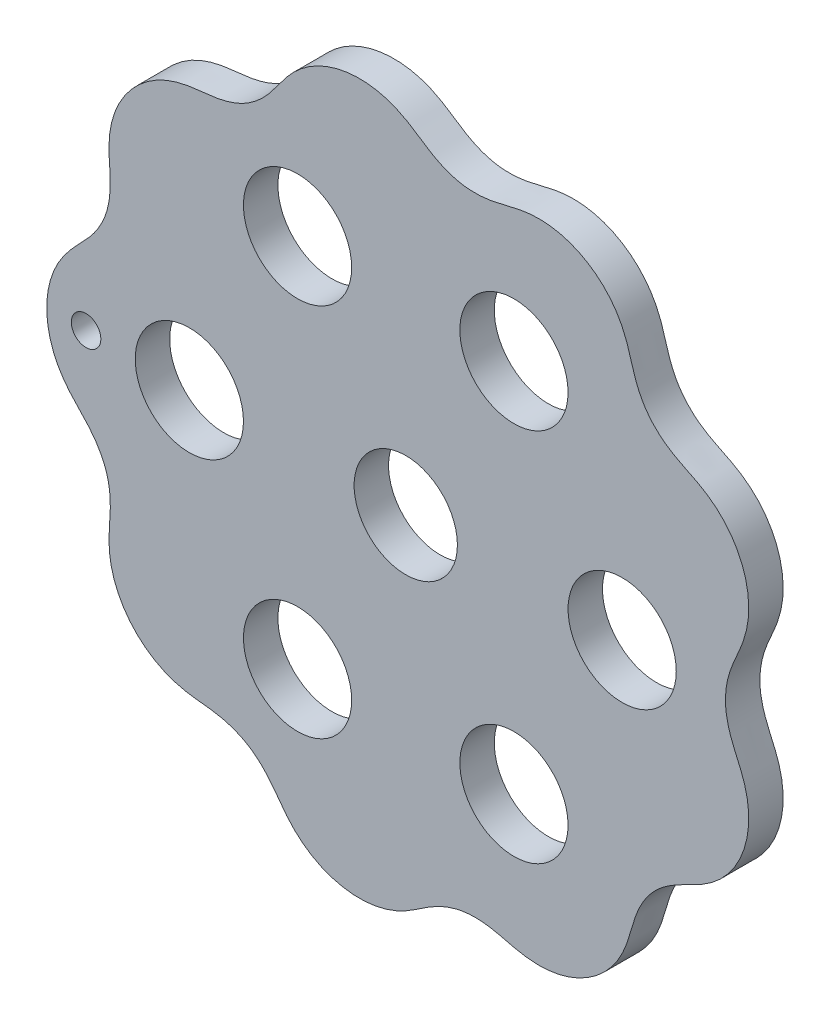
SolidWorks part; units mm, degrees
ref_plane "Front Plane" through (0, 0, 0) normal (0, 0, 1) x (1, 0, 0)
ref_plane "Top Plane" through (0, 0, 0) normal (0, 1, 0) x (1, 0, 0)
ref_plane "Right Plane" through (0, 0, 0) normal (1, 0, 0) x (0, 0, -1)
sketch "Sketch1" plane through (0, 0, 0) normal (0, 0, 1) x (1, 0, 0)
  line L0 (-73, 0) -> (65, 0) construction
  spline S0 degree 4 poles (61.3073, -34.2273) (61.493, -34.1034) (61.8608, -33.8502) (62.401, -33.4542) (63.0962, -32.8933) (63.7568, -32.3065) (64.3822, -31.6959) (64.9718, -31.0638) (65.5256, -30.4127) (66.049, -29.737) (66.541, -29.038) (67.0007, -28.3174) (67.4273, -27.5767) (67.8199, -26.8174) (68.178, -26.0413) (68.5008, -25.2499) (68.7877, -24.4447) (69.0381, -23.6275) (69.2514, -22.7998) (69.4273, -21.9633) (69.5651, -21.1198) (69.6645, -20.2708) (69.7176, -19.5248) (69.7387, -18.8842) (69.74, -18.3502) (69.7313, -17.923) (69.7127, -17.4962) (69.6843, -17.0698) (69.6462, -16.6443) (69.5983, -16.2198) (69.5407, -15.7964) (69.4819, -15.4273) (69.4255, -15.1119) (69.3746, -14.8498) (69.3316, -14.6406) (69.2862, -14.4319) (69.2444, -14.2497) (69.2072, -14.0939) (69.1753, -13.9642) (69.1492, -13.8607) (69.1228, -13.7581) (69.0951, -13.6533) (69.0665, -13.5475) (69.0433, -13.4628) (69.0257, -13.3989) (69.0055, -13.3279) (68.9819, -13.2466) (68.944, -13.1175) (68.9076, -12.9939) (68.9636, -13.1823) (68.9277, -13.0626) (68.8813, -12.9088) (68.8479, -12.7995) (68.8281, -12.7378) (68.803, -12.6599) (68.7773, -12.5799) (68.7411, -12.4684) (68.7054, -12.3603) (68.6699, -12.2562) (68.6201, -12.1128) (68.5664, -11.9595) (68.5026, -11.7817) (68.4128, -11.5396) (68.3173, -11.2884) (68.2213, -11.0447) (68.1025, -10.7498) (67.9816, -10.457) (67.7962, -10.0189) (67.5427, -9.4377) (67.242, -8.7617) (66.9007, -7.9882) (66.6001, -7.2806) (66.3428, -6.6384) (66.1272, -6.0623) (65.9496, -5.5542) (65.7844, -5.042) (65.6328, -4.5255) (65.4957, -4.005) (65.374, -3.4807) (65.2514, -2.868) (65.1386, -2.1654) (65.0487, -1.3722) (64.9973, -0.4888) (64.9947, 0.3961) (65.0411, 1.2797) (65.1356, 2.1595) (65.2772, 3.0327) (65.4938, 4.0386) (65.8091, 5.1683) (66.3609, 6.7584) (67.1956, 8.6804) (68.1864, 10.8265) (69.0064, 13.131) (69.4921, 15.2329) (69.7787, 17.6218) (69.7586, 20.2836) (69.2421, 23.3843) (67.9898, 26.7805) (66.1004, 29.9051) (63.9856, 32.2244) (61.9632, 33.8331) (59.9244, 35.1173) (58.0026, 36.1114) (55.773, 37.1453) (53.1577, 38.6272) (50.6634, 40.6124) (48.1772, 43.6332) (46.5494, 47.2486) (45.6788, 50.853) (44.4877, 54.3714) (42.9782, 57.2636) (40.8374, 60.0002) (38.0491, 62.4028) (34.8563, 64.2263) (31.375, 65.4056) (27.9067, 65.8635) (24.5909, 65.6864) (21.6065, 65.0508) (18.9163, 64.3231) (15.9988, 63.7742) (12.8476, 63.668) (9.7288, 64.2152) (6.802, 65.3881) (4.2464, 66.8988) (1.967, 68.5024) (-0.6182, 70.1232) (-3.6716, 71.428) (-7.0863, 72.1888) (-10.7608, 72.2765) (-14.3856, 71.6601) (-17.8293, 70.3608) (-20.7797, 68.5257) (-23.1904, 66.3276) (-25.5166, 63.4314) (-27.5659, 60.3413) (-30.3273, 57.4962) (-33.6934, 55.5025) (-36.7147, 54.4849) (-39.3098, 54.0465) (-41.384, 53.8369) (-43.1619, 53.6423) (-44.6386, 53.4201) (-46.629, 52.9929) (-49.081, 52.1759) (-51.8634, 50.724) (-54.7375, 48.4165) (-57.1178, 45.5984) (-58.9152, 42.3728) (-59.9875, 39.0487) (-60.4067, 35.7907) (-60.3256, 32.7522) (-60.0723, 29.9661) (-60.0138, 26.959) (-60.4508, 23.7661) (-61.5496, 20.7238) (-63.2538, 17.9882) (-64.9898, 15.9872) (-66.447, 14.4994) (-67.6572, 13.2246) (-68.5997, 12.1464) (-69.5368, 10.932) (-70.4328, 9.5635) (-71.25, 8.0297) (-71.9504, 6.3291) (-72.4801, 4.5677) (-72.8354, 2.7632) (-72.994, 1.139) (-73.0156, -0.2846) (-72.952, -1.4991) (-72.8589, -2.3772) (-72.7459, -3.1254) (-72.6296, -3.7451) (-72.5233, -4.2382) (-72.4038, -4.7283) (-72.2712, -5.2149) (-72.1256, -5.6978) (-71.9669, -6.1766) (-71.7954, -6.651) (-71.6111, -7.1205) (-71.4141, -7.5849) (-71.2047, -8.0437) (-71.0106, -8.4401) (-70.8366, -8.776) (-70.6867, -9.0532) (-70.5638, -9.2734) (-70.4379, -9.4919) (-70.3091, -9.7087) (-70.1775, -9.9238) (-70.0431, -10.1371) (-69.9229, -10.3223) (-69.8185, -10.4796) (-69.712, -10.637) (-69.6251, -10.7635) (-69.5368, -10.8888) (-69.4726, -10.9795) (-69.4329, -11.0351) (-69.3882, -11.0965) (-69.3015, -11.2146) (-69.1776, -11.3824) (-69.3167, -11.195) (-69.2384, -11.3) (-69.142, -11.4289) (-69.0732, -11.5202) (-69.0334, -11.5715) (-68.9831, -11.6363) (-68.9314, -11.7028) (-68.8591, -11.7955) (-68.7884, -11.8852) (-68.7193, -11.9709) (-68.6232, -12.0889) (-68.52, -12.2148) (-68.399, -12.3604) (-68.2314, -12.5575) (-68.0554, -12.7613) (-67.8814, -12.9579) (-67.6684, -13.1949) (-67.4542, -13.4292) (-67.1294, -13.7782) (-66.6913, -14.2385) (-66.1765, -14.7721) (-65.5899, -15.3836) (-65.0645, -15.9471) (-64.6022, -16.464) (-64.202, -16.9328) (-63.8609, -17.3507) (-63.4474, -17.8834) (-63.0529, -18.4304) (-62.6798, -18.9923) (-62.2852, -19.643) (-61.9391, -20.2663) (-61.5838, -20.983) (-61.234, -21.7977) (-60.9299, -22.6305) (-60.6724, -23.4789) (-60.4617, -24.34) (-60.2975, -25.2111) (-60.159, -26.2326) (-60.0706, -27.405) (-60.054, -28.7251) (-60.1161, -30.1879) (-60.1943, -31.2829) (-60.2441, -32.0131) (-60.2664, -32.3783) knots 0 0 0 0 0 0.002911 0.005822 0.008733 0.011644 0.01443 0.017216 0.020002 0.022788 0.025574 0.02836 0.031145 0.033931 0.036717 0.039503 0.042289 0.045074 0.04786 0.050646 0.053432 0.056218 0.059003 0.060396 0.061789 0.063182 0.064575 0.065968 0.067361 0.068753 0.070146 0.071539 0.072235 0.072932 0.073628 0.074324 0.075021 0.075369 0.075717 0.076065 0.076413 0.076762 0.07711 0.077458 0.077632 0.077806 0.07798 0.078154 0.078503 0.078847 0.079019 0.079192 0.079536 0.079881 0.080226 0.080398 0.08057 0.081259 0.081604 0.081948 0.082638 0.083327 0.084016 0.085394 0.086083 0.086773 0.088151 0.089529 0.092286 0.095043 0.097799 0.100556 0.102311 0.104065 0.10582 0.107575 0.109329 0.111084 0.112839 0.114593 0.117477 0.120361 0.123244 0.126128 0.129011 0.131894 0.134777 0.137661 0.142422 0.147183 0.156706 0.164976 0.173246 0.179012 0.184777 0.196307 0.207838 0.219769 0.231702 0.243634 0.2485 0.253366 0.263098 0.271825 0.280552 0.292488 0.304425 0.322381 0.331611 0.340841 0.352772 0.364705 0.376636 0.388536 0.400436 0.412336 0.421971 0.431607 0.440152 0.448697 0.460602 0.472507 0.481053 0.489598 0.499233 0.508869 0.520769 0.532669 0.544569 0.5565 0.568433 0.580364 0.589594 0.598824 0.61678 0.628717 0.640652 0.64938 0.658107 0.662973 0.667839 0.672705 0.677571 0.689503 0.701436 0.713367 0.725341 0.737315 0.749288 0.758622 0.767957 0.776873 0.785788 0.797766 0.809744 0.81866 0.827576 0.832243 0.83691 0.841577 0.846245 0.852231 0.858218 0.864205 0.870192 0.876179 0.882166 0.885454 0.888743 0.892032 0.893676 0.89532 0.896965 0.898609 0.900253 0.901898 0.903542 0.905186 0.906831 0.908475 0.910119 0.911763 0.912586 0.913408 0.91423 0.915052 0.915874 0.916696 0.917518 0.91834 0.918751 0.919162 0.919984 0.920396 0.920601 0.920807 0.921012 0.921218 0.921629 0.921974 0.922147 0.922319 0.922665 0.92301 0.923355 0.923528 0.923701 0.924391 0.924737 0.925082 0.925773 0.926463 0.927154 0.928535 0.929226 0.929917 0.931298 0.932679 0.935442 0.938205 0.940968 0.94373 0.945489 0.947247 0.949006 0.950765 0.954282 0.95604 0.957799 0.960688 0.963577 0.966467 0.969356 0.972245 0.975134 0.978022 0.980911 0.985683 0.990456 0.995228 1 1 1 1 1 construction
  spline S1 degree 4 poles (65, 0) (65, 0.2095) (65.0075, 0.6401) (65.0423, 1.2912) (65.1356, 2.1595) (65.2772, 3.0327) (65.4938, 4.0386) (65.8091, 5.1683) (66.3609, 6.7584) (67.1956, 8.6804) (68.1864, 10.8265) (69.0064, 13.131) (69.4921, 15.2329) (69.7787, 17.6218) (69.7586, 20.2836) (69.2421, 23.3843) (67.9898, 26.7805) (66.1004, 29.9051) (63.9856, 32.2244) (61.9632, 33.8331) (59.9244, 35.1173) (58.0026, 36.1114) (55.773, 37.1453) (53.1577, 38.6272) (50.6634, 40.6124) (48.1772, 43.6332) (46.5494, 47.2486) (45.6788, 50.853) (44.4877, 54.3714) (42.9782, 57.2636) (40.8374, 60.0002) (38.0491, 62.4028) (34.8563, 64.2263) (31.375, 65.4056) (27.9067, 65.8635) (24.5909, 65.6864) (21.6065, 65.0508) (18.9163, 64.3231) (15.9988, 63.7742) (12.8476, 63.668) (9.7288, 64.2152) (6.802, 65.3881) (4.2464, 66.8988) (1.967, 68.5024) (-0.6182, 70.1232) (-3.6716, 71.428) (-7.0863, 72.1888) (-10.7608, 72.2765) (-14.3856, 71.6601) (-17.8293, 70.3608) (-20.7797, 68.5257) (-23.1904, 66.3276) (-25.5166, 63.4314) (-27.5659, 60.3413) (-30.3273, 57.4962) (-33.6934, 55.5025) (-36.7147, 54.4849) (-39.3098, 54.0465) (-41.384, 53.8369) (-43.1619, 53.6423) (-44.6386, 53.4201) (-46.629, 52.9929) (-49.081, 52.1759) (-51.8634, 50.724) (-54.7375, 48.4165) (-57.1178, 45.5984) (-58.9152, 42.3728) (-59.9875, 39.0487) (-60.4067, 35.7907) (-60.3256, 32.7522) (-60.0723, 29.9661) (-60.0138, 26.959) (-60.4508, 23.7661) (-61.5496, 20.7238) (-63.2538, 17.9882) (-64.9898, 15.9872) (-66.447, 14.4994) (-67.6572, 13.2246) (-68.5997, 12.1464) (-69.5368, 10.932) (-70.4328, 9.5635) (-71.25, 8.0297) (-71.9504, 6.3291) (-72.4801, 4.5677) (-72.8354, 2.7632) (-72.9698, 1.3871) (-72.9999, 0.4657) (-73, 0.0033) (-73, 0) knots 0.123395 0.123395 0.123395 0.123395 0.123395 0.126128 0.129011 0.131894 0.134777 0.137661 0.142422 0.147183 0.156706 0.164976 0.173246 0.179012 0.184777 0.196307 0.207838 0.219769 0.231702 0.243634 0.2485 0.253366 0.263098 0.271825 0.280552 0.292488 0.304425 0.322381 0.331611 0.340841 0.352772 0.364705 0.376636 0.388536 0.400436 0.412336 0.421971 0.431607 0.440152 0.448697 0.460602 0.472507 0.481053 0.489598 0.499233 0.508869 0.520769 0.532669 0.544569 0.5565 0.568433 0.580364 0.589594 0.598824 0.61678 0.628717 0.640652 0.64938 0.658107 0.662973 0.667839 0.672705 0.677571 0.689503 0.701436 0.713367 0.725341 0.737315 0.749288 0.758622 0.767957 0.776873 0.785788 0.797766 0.809744 0.81866 0.827576 0.832243 0.83691 0.841577 0.846245 0.852231 0.858218 0.864205 0.870192 0.876179 0.882166 0.882209 0.882209 0.882209 0.882209 0.882209 construction
  spline S2 degree 4 poles (65, 0) (65, -0.2095) (65.0075, -0.6401) (65.0423, -1.2912) (65.1356, -2.1595) (65.2772, -3.0327) (65.4938, -4.0386) (65.8091, -5.1683) (66.3609, -6.7584) (67.1956, -8.6804) (68.1864, -10.8265) (69.0064, -13.131) (69.4921, -15.2329) (69.7787, -17.6218) (69.7586, -20.2836) (69.2421, -23.3843) (67.9898, -26.7805) (66.1004, -29.9051) (63.9856, -32.2244) (61.9632, -33.8331) (59.9244, -35.1173) (58.0026, -36.1114) (55.773, -37.1453) (53.1577, -38.6272) (50.6634, -40.6124) (48.1772, -43.6332) (46.5494, -47.2486) (45.6788, -50.853) (44.4877, -54.3714) (42.9782, -57.2636) (40.8374, -60.0002) (38.0491, -62.4028) (34.8563, -64.2263) (31.375, -65.4056) (27.9067, -65.8635) (24.5909, -65.6864) (21.6065, -65.0508) (18.9163, -64.3231) (15.9988, -63.7742) (12.8476, -63.668) (9.7288, -64.2152) (6.802, -65.3881) (4.2464, -66.8988) (1.967, -68.5024) (-0.6182, -70.1232) (-3.6716, -71.428) (-7.0863, -72.1888) (-10.7608, -72.2765) (-14.3856, -71.6601) (-17.8293, -70.3608) (-20.7797, -68.5257) (-23.1904, -66.3276) (-25.5166, -63.4314) (-27.5659, -60.3413) (-30.3273, -57.4962) (-33.6934, -55.5025) (-36.7147, -54.4849) (-39.3098, -54.0465) (-41.384, -53.8369) (-43.1619, -53.6423) (-44.6386, -53.4201) (-46.629, -52.9929) (-49.081, -52.1759) (-51.8634, -50.724) (-54.7375, -48.4165) (-57.1178, -45.5984) (-58.9152, -42.3728) (-59.9875, -39.0487) (-60.4067, -35.7907) (-60.3256, -32.7522) (-60.0723, -29.9661) (-60.0138, -26.959) (-60.4508, -23.7661) (-61.5496, -20.7238) (-63.2538, -17.9882) (-64.9898, -15.9872) (-66.447, -14.4994) (-67.6572, -13.2246) (-68.5997, -12.1464) (-69.5368, -10.932) (-70.4328, -9.5635) (-71.25, -8.0297) (-71.9504, -6.3291) (-72.4801, -4.5677) (-72.8354, -2.7632) (-72.9698, -1.3871) (-72.9999, -0.4657) (-73, -0.0033) (-73, 0) knots 0.123395 0.123395 0.123395 0.123395 0.123395 0.126128 0.129011 0.131894 0.134777 0.137661 0.142422 0.147183 0.156706 0.164976 0.173246 0.179012 0.184777 0.196307 0.207838 0.219769 0.231702 0.243634 0.2485 0.253366 0.263098 0.271825 0.280552 0.292488 0.304425 0.322381 0.331611 0.340841 0.352772 0.364705 0.376636 0.388536 0.400436 0.412336 0.421971 0.431607 0.440152 0.448697 0.460602 0.472507 0.481053 0.489598 0.499233 0.508869 0.520769 0.532669 0.544569 0.5565 0.568433 0.580364 0.589594 0.598824 0.61678 0.628717 0.640652 0.64938 0.658107 0.662973 0.667839 0.672705 0.677571 0.689503 0.701436 0.713367 0.725341 0.737315 0.749288 0.758622 0.767957 0.776873 0.785788 0.797766 0.809744 0.81866 0.827576 0.832243 0.83691 0.841577 0.846245 0.852231 0.858218 0.864205 0.870192 0.876179 0.882166 0.882209 0.882209 0.882209 0.882209 0.882209 construction
  spline S3 degree 4 poles (65, 0.0008) (65, 0.2101) (65.0075, 0.6405) (65.0423, 1.2914) (65.1356, 2.1595) (65.2772, 3.0327) (65.4938, 4.0386) (65.8091, 5.1683) (66.3609, 6.7584) (67.1956, 8.6804) (68.1864, 10.8265) (69.0064, 13.131) (69.4921, 15.2329) (69.7787, 17.6218) (69.7586, 20.2836) (69.2421, 23.3843) (67.9898, 26.7805) (66.1004, 29.9051) (63.9856, 32.2244) (61.9632, 33.8331) (59.9244, 35.1173) (58.0026, 36.1114) (55.773, 37.1453) (53.1577, 38.6272) (50.6634, 40.6124) (48.1772, 43.6332) (46.5494, 47.2486) (45.6788, 50.853) (44.4877, 54.3714) (42.9782, 57.2636) (40.8374, 60.0002) (38.0491, 62.4028) (34.8563, 64.2263) (31.375, 65.4056) (27.9067, 65.8635) (24.5909, 65.6864) (21.6065, 65.0508) (18.9163, 64.3231) (15.9988, 63.7742) (12.8476, 63.668) (9.7288, 64.2152) (6.802, 65.3881) (4.2464, 66.8988) (1.967, 68.5024) (-0.6182, 70.1232) (-3.6716, 71.428) (-7.0863, 72.1888) (-10.7608, 72.2765) (-14.3856, 71.6601) (-17.8293, 70.3608) (-20.7797, 68.5257) (-23.1904, 66.3276) (-25.5166, 63.4314) (-27.5659, 60.3413) (-30.3273, 57.4962) (-33.6934, 55.5025) (-36.7147, 54.4849) (-39.3098, 54.0465) (-41.384, 53.8369) (-43.1619, 53.6423) (-44.6386, 53.4201) (-46.629, 52.9929) (-49.081, 52.1759) (-51.8634, 50.724) (-54.7375, 48.4165) (-57.1178, 45.5984) (-58.9152, 42.3728) (-59.9875, 39.0487) (-60.4067, 35.7907) (-60.3256, 32.7522) (-60.0723, 29.9661) (-60.0138, 26.959) (-60.4508, 23.7661) (-61.5496, 20.7238) (-63.2538, 17.9882) (-64.9898, 15.9872) (-66.447, 14.4994) (-67.6572, 13.2246) (-68.5997, 12.1464) (-69.5368, 10.932) (-70.4328, 9.5635) (-71.25, 8.0297) (-71.9504, 6.3291) (-72.4801, 4.5677) (-72.8354, 2.7632) (-72.9698, 1.3874) (-72.9999, 0.4662) (-73, 0.004) (-73, 0.001) (-73, 0.0008) (-73, 0.0006) (-73, 0.0003) (-73, 0) (-73, -0.0003) (-73, -0.0006) (-73, -0.0008) (-73, -0.001) (-73, -0.004) (-72.9999, -0.4662) (-72.9698, -1.3874) (-72.8354, -2.7632) (-72.4801, -4.5677) (-71.9504, -6.3291) (-71.25, -8.0297) (-70.4328, -9.5635) (-69.5368, -10.932) (-68.5997, -12.1464) (-67.6572, -13.2246) (-66.447, -14.4994) (-64.9898, -15.9872) (-63.2538, -17.9882) (-61.5496, -20.7238) (-60.4508, -23.7661) (-60.0138, -26.959) (-60.0723, -29.9661) (-60.3256, -32.7522) (-60.4067, -35.7907) (-59.9875, -39.0487) (-58.9152, -42.3728) (-57.1178, -45.5984) (-54.7375, -48.4165) (-51.8634, -50.724) (-49.081, -52.1759) (-46.629, -52.9929) (-44.6386, -53.4201) (-43.1619, -53.6423) (-41.384, -53.8369) (-39.3098, -54.0465) (-36.7147, -54.4849) (-33.6934, -55.5025) (-30.3273, -57.4962) (-27.5659, -60.3413) (-25.5166, -63.4314) (-23.1904, -66.3276) (-20.7797, -68.5257) (-17.8293, -70.3608) (-14.3856, -71.6601) (-10.7608, -72.2765) (-7.0863, -72.1888) (-3.6716, -71.428) (-0.6182, -70.1232) (1.967, -68.5024) (4.2464, -66.8988) (6.802, -65.3881) (9.7288, -64.2152) (12.8476, -63.668) (15.9988, -63.7742) (18.9163, -64.3231) (21.6065, -65.0508) (24.5909, -65.6864) (27.9067, -65.8635) (31.375, -65.4056) (34.8563, -64.2263) (38.0491, -62.4028) (40.8374, -60.0002) (42.9782, -57.2636) (44.4877, -54.3714) (45.6788, -50.853) (46.5494, -47.2486) (48.1772, -43.6332) (50.6634, -40.6124) (53.1577, -38.6272) (55.773, -37.1453) (58.0026, -36.1114) (59.9244, -35.1173) (61.9632, -33.8331) (63.9856, -32.2244) (66.1004, -29.9051) (67.9898, -26.7805) (69.2421, -23.3843) (69.7586, -20.2836) (69.7787, -17.6218) (69.4921, -15.2329) (69.0064, -13.131) (68.1864, -10.8265) (67.1956, -8.6804) (66.3609, -6.7584) (65.8091, -5.1683) (65.4938, -4.0386) (65.2772, -3.0327) (65.1356, -2.1595) (65.0423, -1.2914) (65.0075, -0.6405) (65, -0.2101) (65, -0.0008) (65, -0.0007) (65, -0.0005) (65, -0.0003) (65, 0) (65, 0.0003) (65, 0.0005) (65, 0.0007) (65, 0.0008) (65, 0.2101) (65.0075, 0.6405) (65.0423, 1.2914) knots -0.000001 0 0 0 0 0.001799 0.003699 0.005598 0.007498 0.009398 0.012535 0.015673 0.021947 0.027397 0.032846 0.036645 0.040444 0.048042 0.055639 0.063501 0.071364 0.079226 0.082432 0.085639 0.092051 0.097802 0.103553 0.111418 0.119283 0.131115 0.137196 0.143278 0.15114 0.159003 0.166865 0.174706 0.182547 0.190388 0.196737 0.203086 0.208717 0.214347 0.222192 0.230036 0.235667 0.241298 0.247647 0.253996 0.261837 0.269678 0.277519 0.285381 0.293244 0.301106 0.307188 0.313269 0.325101 0.332966 0.340831 0.346582 0.352333 0.355539 0.358745 0.361952 0.365158 0.37302 0.380882 0.388745 0.396634 0.404524 0.412414 0.418564 0.424715 0.43059 0.436464 0.444357 0.452249 0.458124 0.463999 0.467075 0.47015 0.473225 0.476301 0.480245 0.48419 0.488135 0.49208 0.496025 0.49997 0.499996 0.499996 0.499996 0.499996 0.499998 0.499998 0.499999 0.499999 0.5 0.5 0.5 0.5 0.500027 0.503972 0.507916 0.511861 0.515806 0.519751 0.523696 0.526771 0.529847 0.532922 0.535997 0.541872 0.547747 0.555639 0.563532 0.569407 0.575281 0.581432 0.587583 0.595473 0.603362 0.611252 0.619114 0.626976 0.634839 0.638045 0.641251 0.644458 0.647664 0.653415 0.659165 0.66703 0.674896 0.686727 0.692809 0.698891 0.706753 0.714615 0.722477 0.730318 0.73816 0.746001 0.75235 0.758699 0.764329 0.76996 0.777805 0.785649 0.79128 0.796911 0.803259 0.809608 0.81745 0.825291 0.833132 0.840994 0.848856 0.856719 0.8628 0.868882 0.880714 0.888579 0.896444 0.902195 0.907945 0.914358 0.917564 0.92077 0.928633 0.936495 0.944357 0.951955 0.959552 0.963351 0.96715 0.9726 0.978049 0.984324 0.987461 0.990598 0.992498 0.994398 0.996298 0.998198 0.999997 0.999997 0.999997 0.999997 0.999998 0.999998 0.999999 0.999999 1 1 1 1 1.001799 1.003699 1.005598 1.007498 only from (65, 0.0008) to (65, 0.0008)
extrude "Boss-Extrude1" add sketch "Sketch1" along normal blind 7
sketch "Sketch2" plane through (0, 0, 7) normal (0, 0, 1) x (1, 0, 0)
  line L0 (0, 0) -> (-73, 0) construction
  circle A1 centre (-44, 0) radius 11
  circle A2 centre (0, 0) radius 44 construction
  circle A26 centre (-22, 38.1051) radius 11
  circle A27 centre (22, 38.1051) radius 11
  circle A28 centre (44, 0) radius 11
  circle A29 centre (22, -38.1051) radius 11
  circle A30 centre (-22, -38.1051) radius 11
  spline S0 degree 4 poles (65, 0.0008) (65, 0.2101) (65.0075, 0.6405) (65.0423, 1.2914) (65.1356, 2.1595) (65.2772, 3.0327) (65.4938, 4.0386) (65.8091, 5.1683) (66.3609, 6.7584) (67.1956, 8.6804) (68.1864, 10.8265) (69.0064, 13.131) (69.4921, 15.2329) (69.7787, 17.6218) (69.7586, 20.2836) (69.2421, 23.3843) (67.9898, 26.7805) (66.1004, 29.9051) (63.9856, 32.2244) (61.9632, 33.8331) (59.9244, 35.1173) (58.0026, 36.1114) (55.773, 37.1453) (53.1577, 38.6272) (50.6634, 40.6124) (48.1772, 43.6332) (46.5494, 47.2486) (45.6788, 50.853) (44.4877, 54.3714) (42.9782, 57.2636) (40.8374, 60.0002) (38.0491, 62.4028) (34.8563, 64.2263) (31.375, 65.4056) (27.9067, 65.8635) (24.5909, 65.6864) (21.6065, 65.0508) (18.9163, 64.3231) (15.9988, 63.7742) (12.8476, 63.668) (9.7288, 64.2152) (6.802, 65.3881) (4.2464, 66.8988) (1.967, 68.5024) (-0.6182, 70.1232) (-3.6716, 71.428) (-7.0863, 72.1888) (-10.7608, 72.2765) (-14.3856, 71.6601) (-17.8293, 70.3608) (-20.7797, 68.5257) (-23.1904, 66.3276) (-25.5166, 63.4314) (-27.5659, 60.3413) (-30.3273, 57.4962) (-33.6934, 55.5025) (-36.7147, 54.4849) (-39.3098, 54.0465) (-41.384, 53.8369) (-43.1619, 53.6423) (-44.6386, 53.4201) (-46.629, 52.9929) (-49.081, 52.1759) (-51.8634, 50.724) (-54.7375, 48.4165) (-57.1178, 45.5984) (-58.9152, 42.3728) (-59.9875, 39.0487) (-60.4067, 35.7907) (-60.3256, 32.7522) (-60.0723, 29.9661) (-60.0138, 26.959) (-60.4508, 23.7661) (-61.5496, 20.7238) (-63.2538, 17.9882) (-64.9898, 15.9872) (-66.447, 14.4994) (-67.6572, 13.2246) (-68.5997, 12.1464) (-69.5368, 10.932) (-70.4328, 9.5635) (-71.25, 8.0297) (-71.9504, 6.3291) (-72.4801, 4.5677) (-72.8354, 2.7632) (-72.9698, 1.3874) (-72.9999, 0.4662) (-73, 0.004) (-73, 0.001) (-73, 0.0008) (-73, 0.0006) (-73, 0.0003) (-73, 0) (-73, -0.0003) (-73, -0.0006) (-73, -0.0008) (-73, -0.001) (-73, -0.004) (-72.9999, -0.4662) (-72.9698, -1.3874) (-72.8354, -2.7632) (-72.4801, -4.5677) (-71.9504, -6.3291) (-71.25, -8.0297) (-70.4328, -9.5635) (-69.5368, -10.932) (-68.5997, -12.1464) (-67.6572, -13.2246) (-66.447, -14.4994) (-64.9898, -15.9872) (-63.2538, -17.9882) (-61.5496, -20.7238) (-60.4508, -23.7661) (-60.0138, -26.959) (-60.0723, -29.9661) (-60.3256, -32.7522) (-60.4067, -35.7907) (-59.9875, -39.0487) (-58.9152, -42.3728) (-57.1178, -45.5984) (-54.7375, -48.4165) (-51.8634, -50.724) (-49.081, -52.1759) (-46.629, -52.9929) (-44.6386, -53.4201) (-43.1619, -53.6423) (-41.384, -53.8369) (-39.3098, -54.0465) (-36.7147, -54.4849) (-33.6934, -55.5025) (-30.3273, -57.4962) (-27.5659, -60.3413) (-25.5166, -63.4314) (-23.1904, -66.3276) (-20.7797, -68.5257) (-17.8293, -70.3608) (-14.3856, -71.6601) (-10.7608, -72.2765) (-7.0863, -72.1888) (-3.6716, -71.428) (-0.6182, -70.1232) (1.967, -68.5024) (4.2464, -66.8988) (6.802, -65.3881) (9.7288, -64.2152) (12.8476, -63.668) (15.9988, -63.7742) (18.9163, -64.3231) (21.6065, -65.0508) (24.5909, -65.6864) (27.9067, -65.8635) (31.375, -65.4056) (34.8563, -64.2263) (38.0491, -62.4028) (40.8374, -60.0002) (42.9782, -57.2636) (44.4877, -54.3714) (45.6788, -50.853) (46.5494, -47.2486) (48.1772, -43.6332) (50.6634, -40.6124) (53.1577, -38.6272) (55.773, -37.1453) (58.0026, -36.1114) (59.9244, -35.1173) (61.9632, -33.8331) (63.9856, -32.2244) (66.1004, -29.9051) (67.9898, -26.7805) (69.2421, -23.3843) (69.7586, -20.2836) (69.7787, -17.6218) (69.4921, -15.2329) (69.0064, -13.131) (68.1864, -10.8265) (67.1956, -8.6804) (66.3609, -6.7584) (65.8091, -5.1683) (65.4938, -4.0386) (65.2772, -3.0327) (65.1356, -2.1595) (65.0423, -1.2914) (65.0075, -0.6405) (65, -0.2101) (65, -0.0008) (65, -0.0007) (65, -0.0005) (65, -0.0003) (65, 0) (65, 0.0003) (65, 0.0005) (65, 0.0007) (65, 0.0008) (65, 0.2101) (65.0075, 0.6405) (65.0423, 1.2914) knots -0.000001 0 0 0 0 0.001799 0.003699 0.005598 0.007498 0.009398 0.012535 0.015673 0.021947 0.027397 0.032846 0.036645 0.040444 0.048042 0.055639 0.063501 0.071364 0.079226 0.082432 0.085639 0.092051 0.097802 0.103553 0.111418 0.119283 0.131115 0.137196 0.143278 0.15114 0.159003 0.166865 0.174706 0.182547 0.190388 0.196737 0.203086 0.208717 0.214347 0.222192 0.230036 0.235667 0.241298 0.247647 0.253996 0.261837 0.269678 0.277519 0.285381 0.293244 0.301106 0.307188 0.313269 0.325101 0.332966 0.340831 0.346582 0.352333 0.355539 0.358745 0.361952 0.365158 0.37302 0.380882 0.388745 0.396634 0.404524 0.412414 0.418564 0.424715 0.43059 0.436464 0.444357 0.452249 0.458124 0.463999 0.467075 0.47015 0.473225 0.476301 0.480245 0.48419 0.488135 0.49208 0.496025 0.49997 0.499996 0.499996 0.499996 0.499996 0.499998 0.499998 0.499999 0.499999 0.5 0.5 0.5 0.5 0.500027 0.503972 0.507916 0.511861 0.515806 0.519751 0.523696 0.526771 0.529847 0.532922 0.535997 0.541872 0.547747 0.555639 0.563532 0.569407 0.575281 0.581432 0.587583 0.595473 0.603362 0.611252 0.619114 0.626976 0.634839 0.638045 0.641251 0.644458 0.647664 0.653415 0.659165 0.66703 0.674896 0.686727 0.692809 0.698891 0.706753 0.714615 0.722477 0.730318 0.73816 0.746001 0.75235 0.758699 0.764329 0.76996 0.777805 0.785649 0.79128 0.796911 0.803259 0.809608 0.81745 0.825291 0.833132 0.840994 0.848856 0.856719 0.8628 0.868882 0.880714 0.888579 0.896444 0.902195 0.907945 0.914358 0.917564 0.92077 0.928633 0.936495 0.944357 0.951955 0.959552 0.963351 0.96715 0.9726 0.978049 0.984324 0.987461 0.990598 0.992498 0.994398 0.996298 0.998198 0.999997 0.999997 0.999997 0.999997 0.999998 0.999998 0.999999 0.999999 1 1 1 1 1.001799 1.003699 1.005598 1.007498 only from (65, 0.0008) to (65, 0.0008) construction
  point P5 (-44, 0)
  point P17 (0, 0)
  point P19 (0, 0)
  point P25 (0, 0)
  dimension "D1" = 88
  dimension "D3" = 22
  dimension "D2" = 6
extrude "Cut-Extrude1" cut sketch "Sketch2" against normal through all
sketch "Sketch3" plane through (0, 0, 7) normal (0, 0, 1) x (1, 0, 0)
  circle A0 centre (0, 0) radius 10.5
  dimension "D1" = 21
extrude "Cut-Extrude2" cut sketch "Sketch3" against normal through all
sketch "Sketch4" plane through (0, 0, 7) normal (0, 0, 1) x (1, 0, 0)
  line L0 (0, 0) -> (-65, 0) construction
  circle A0 centre (-65, 0) radius 3
  dimension "D1" = 6
  dimension "D2" = 65
extrude "Cut-Extrude3" cut sketch "Sketch4" against normal through all
